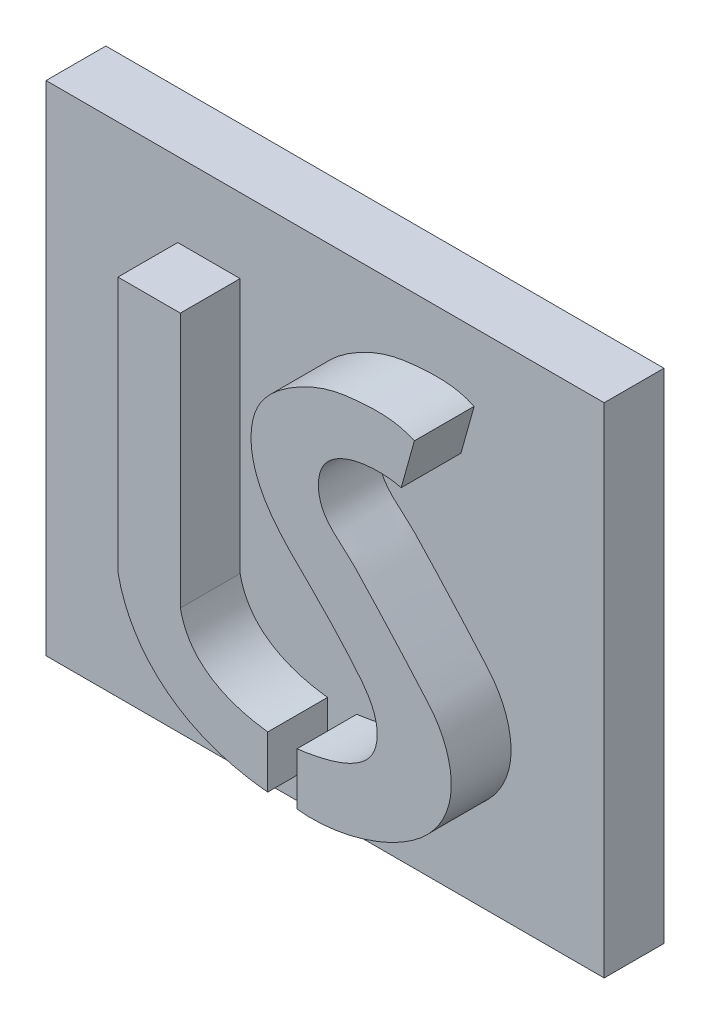
SolidWorks part; units mm, degrees
ref_plane "Plano frontal" through (0, 0, 0) normal (0, 0, 1) x (1, 0, 0)
ref_plane "Plano superior" through (0, 0, 0) normal (0, 1, 0) x (1, 0, 0)
ref_plane "Plano direito" through (0, 0, 0) normal (1, 0, 0) x (0, 0, -1)
sketch "Esboço2" plane through (0, 0, 0) normal (0, 0, 1) x (1, 0, 0)
  line L1 (-29.5827, 16.5561) -> (-1.5774, 16.5561)
  line L2 (-29.5827, 16.5561) -> (-29.5827, -8.4439)
  line L3 (-29.5827, -8.4439) -> (-1.5774, -8.4439)
  line L4 (-1.5774, 16.5561) -> (-1.5774, -8.4439)
  dimension "D1" = 25
extrude "Ressalto-extrusão2" add sketch "Esboço2" along normal blind 3 separate body
sketch "Esboço3" plane through (0, 0, 3) normal (0, 0, 1) x (1, 0, 0)
  line L0 (-22.9765, 12.8178) -> (-19.8443, 12.8178)
  line L1 (-19.8443, 12.8178) -> (-19.8443, 0)
  line L2 (-22.9765, 12.8178) -> (-22.9765, 0)
  line L3 (-15.4592, -5.8073) -> (-15.4592, -3.1912)
  line L4 (-8.7624, 10.7701) -> (-8.1017, 13.1376)
  line L5 (-13.993, -3.1912) -> (-13.993, -5.8073)
  spline S0 degree 3 poles (-19.8443, 0) (-19.5543, -1.4412) (-18.4199, -2.8284) (-15.4592, -3.1912) knots 0 0 0 0 1 1 1 1
  spline S1 degree 3 poles (-22.9765, 0) (-22.343, -3.1194) (-19.6729, -5.4302) (-15.4592, -5.8073) knots 0 0 0 0 1 1 1 1
  spline S2 degree 3 poles (-13.993, -5.8073) (-11.984, -6.0543) (-7.9756, -4.8432) (-6.4169, -2.3463) (-6.1419, -0.4427) (-6.5784, 1.1246) (-8.6119, 3.4788) (-9.7375, 4.7076) (-11.5567, 6.6734) (-12.9516, 7.6098) (-13.0065, 9.7895) (-11.2133, 11.0081) (-9.3979, 10.9474) (-8.7624, 10.7701) knots 0 0 0 0 0.199547 0.300844 0.326269 0.428378 0.465296 0.658523 0.691498 0.770893 0.837393 0.898087 1 1 1 1
  spline S3 degree 3 poles (-8.1017, 13.1376) (-8.9248, 13.5189) (-10.3337, 13.5345) (-12.4694, 13.2847) (-14.3643, 12.4378) (-16.197, 10.896) (-16.4329, 8.5122) (-15.4103, 6.1856) (-13.2809, 4.2217) (-11.3572, 2.1704) (-9.8865, 0.3308) (-10.0232, -2.5895) (-12.9475, -3.0464) (-13.993, -3.1912) knots 0 0 0 0 0.095975 0.152802 0.233792 0.321873 0.398878 0.476755 0.59289 0.710882 0.789461 0.84063 1 1 1 1
extrude "Ressalto-extrusão3" add sketch "Esboço3" along normal blind 3
